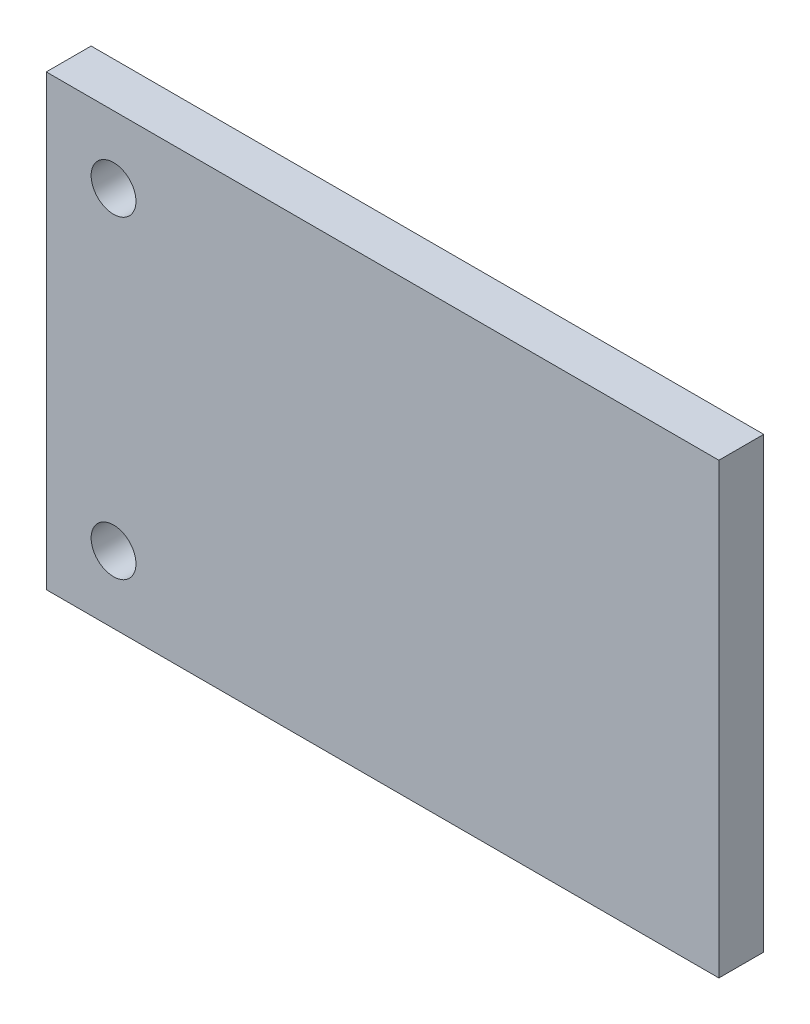
SolidWorks part; units mm, degrees
ref_plane "Płaszczyzna przednia" through (0, 0, 0) normal (0, 0, 1) x (1, 0, 0)
ref_plane "Płaszczyzna górna" through (0, 0, 0) normal (0, 1, 0) x (1, 0, 0)
ref_plane "Płaszczyzna prawa" through (0, 0, 0) normal (1, 0, 0) x (0, 0, -1)
sketch "Szkic1" plane through (0, 0, 0) normal (0, 0, 1) x (1, 0, 0)
  line L1 (0, 0) -> (300, 0)
  line L2 (0, 0) -> (0, -200)
  line L3 (0, -200) -> (300, -200)
  line L4 (300, 0) -> (300, -200)
  circle A0 centre (30, -170) radius 10
  circle A1 centre (30, -30) radius 10
  dimension "D3" = 20
  dimension "D6" = 20
  dimension "D1" = 300
  dimension "D2" = 200
  dimension "D4" = 30
  dimension "D5" = 30
  dimension "D7" = 30
  dimension "D8" = 30
extrude "Dodanie-wyciągnięcie1" add sketch "Szkic1" along normal blind 20
